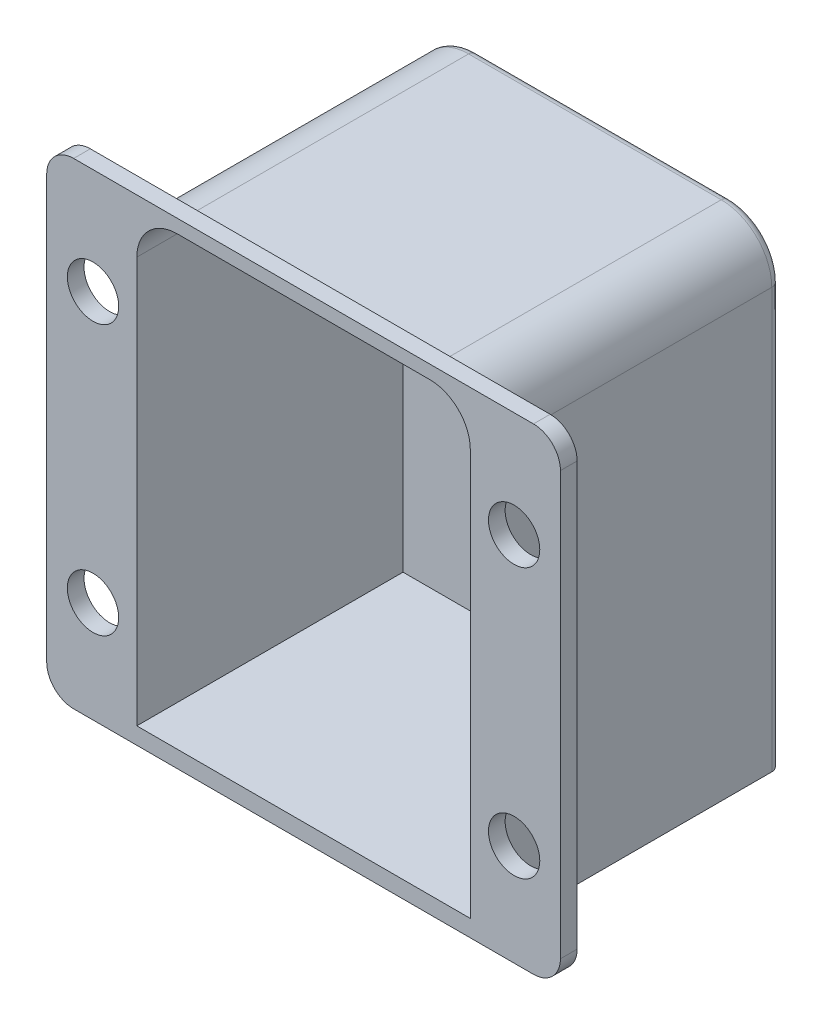
SolidWorks part; units mm, degrees
material "PW60:36:C1:0:1:2:Re:26:"
ref_plane "Plane1" through (0, 0, 0) normal (0, 0, 1) x (1, 0, 0)
ref_plane "Plane2" through (0, 0, 0) normal (0, 1, 0) x (1, 0, 0)
ref_plane "Plane3" through (0, 0, 0) normal (1, 0, 0) x (0, 0, -1)
sketch "Sketch1" plane through (0, 0, 0) normal (0, 0, 1) x (1, 0, 0)
  line L0 (0, 6.2738) -> (0, -25) construction
  line L1 (-13.6498, 6.2738) -> (13.6498, 6.2738)
  line L2 (13.6498, -22.0262) -> (-13.6498, -22.0262)
  line L3 (15.25, -20.426) -> (15.25, 4.6736)
  line L4 (-15.25, -20.426) -> (-15.25, 4.6736)
  line L5 (-13.6498, 4.6736) -> (13.6498, -20.426) construction
  arc A0 (13.6498, 6.2738) -> (15.25, 4.6736) centre (13.6498, 4.6736) cw
  arc A1 (13.6498, -22.0262) -> (15.25, -20.426) centre (13.6498, -20.426) ccw
  arc A2 (-15.25, -20.426) -> (-13.6498, -22.0262) centre (-13.6498, -20.426) ccw
  arc A3 (-13.6498, 6.2738) -> (-15.25, 4.6736) centre (-13.6498, 4.6736) ccw
  point P9 (15.25, 6.2738)
  point P12 (15.25, -22.0262)
  point P15 (-15.25, -22.0262)
  point P18 (-15.25, 6.2738)
  dimension "D4" = 1.6002
  dimension "D1" = 30.5
  dimension "D2" = 28.3
extrude "Base-Extrude" add sketch "Sketch1" against normal blind 0.9906
sketch "Sketch8" plane through (0, 0, 0) normal (0, 0, 1) x (1, 0, 0)
  line L0 (0, 8.3566) -> (0, -9.525) construction
  line L1 (-13.6498, 6.2738) -> (13.6498, 6.2738) construction
  circle A0 centre (12.5, 0) radius 1.524
  circle A1 centre (-12.5, 0) radius 1.524
  dimension "D1" = 3.048
  dimension "D3" = 6.2738
  dimension "D2" = 25
extrude "Cut-Extrude4" cut sketch "Sketch8" against normal through all
ref_plane "Plane4" through (4.826, 0, 0) normal (1, 0, 0) x (0, 0, -1)
sketch "Sketch14" plane through (0, 0, -0.9906) normal (0, 0, -1) x (-1, 0, 0)
  line L0 (-10.5, 3.0738) -> (-10.5, -21.8419)
  line L1 (-10.5, -21.8419) -> (10.5, -21.8419)
  line L2 (10.5, -21.8419) -> (10.5, 3.0738)
  line L3 (-13.6498, -22.0262) -> (13.6498, -22.0262) construction
  line L4 (13.6498, 6.2738) -> (-13.6498, 6.2738) construction
  line L7 (0, 0) -> (0, 10.129) construction
  line L12 (7.5, 6.0738) -> (-7.5, 6.0738)
  arc A8 (7.5, 6.0738) -> (10.5, 3.0738) centre (7.5, 3.0738) cw
  arc A11 (-10.5, 3.0738) -> (-7.5, 6.0738) centre (-7.5, 3.0738) cw
  dimension "D5" = 3
  dimension "D6" = 3
  dimension "D1" = 0.1843
  dimension "D2" = 0.2
  dimension "D3" = 10.5
  dimension "D4" = 21
extrude "Boss-Extrude5" add sketch "Sketch14" along normal blind 16.8148
fillet "Fillet3" radius 0.508 5 edges at (-9.6213, 5.1951, -17.8054) (9.6213, 5.1951, -17.8054) (-10.5, -9.384, -17.8054) (0, 6.0738, -17.8054) (10.5, -9.384, -17.8054)
sketch "Sketch15" plane through (0, 0, 0) normal (0, 0, 1) x (1, 0, 0)
  line L3 (9.9, -21.0262) -> (-9.9, -21.0262)
  line L4 (13.6498, -22.0262) -> (-13.6498, -22.0262) construction
  line L6 (9.9, 3.0738) -> (9.9, -21.8419)
  line L7 (-7.5, 5.4738) -> (7.5, 5.4738)
  line L8 (-9.9, -21.8419) -> (-9.9, 3.0738)
  line L9 (9.9, 3.0738) -> (9.9, -21.0262)
  line L10 (-7.5, 5.4738) -> (7.5, 5.4738)
  line L11 (-9.9, -21.0262) -> (-9.9, 3.0738)
  arc A4 (9.9, 3.0738) -> (7.5, 5.4738) centre (7.5, 3.0738) ccw
  arc A5 (-7.5, 5.4738) -> (-9.9, 3.0738) centre (-7.5, 3.0738) ccw
  arc A6 (9.9, 3.0738) -> (7.5, 5.4738) centre (7.5, 3.0738) ccw
  arc A7 (-7.5, 5.4738) -> (-9.9, 3.0738) centre (-7.5, 3.0738) ccw
  dimension "D2" = 1
  dimension "D1" = 0.6
extrude "Cut-Extrude5" cut sketch "Sketch15" against normal offset from surface (15.8054 mm away) 2 up to face at (0, -4.2287, -17.8054)
pattern_linear "LPattern1" count 2 spacing 16 along (0, -1, 0) of "Cut-Extrude4"
